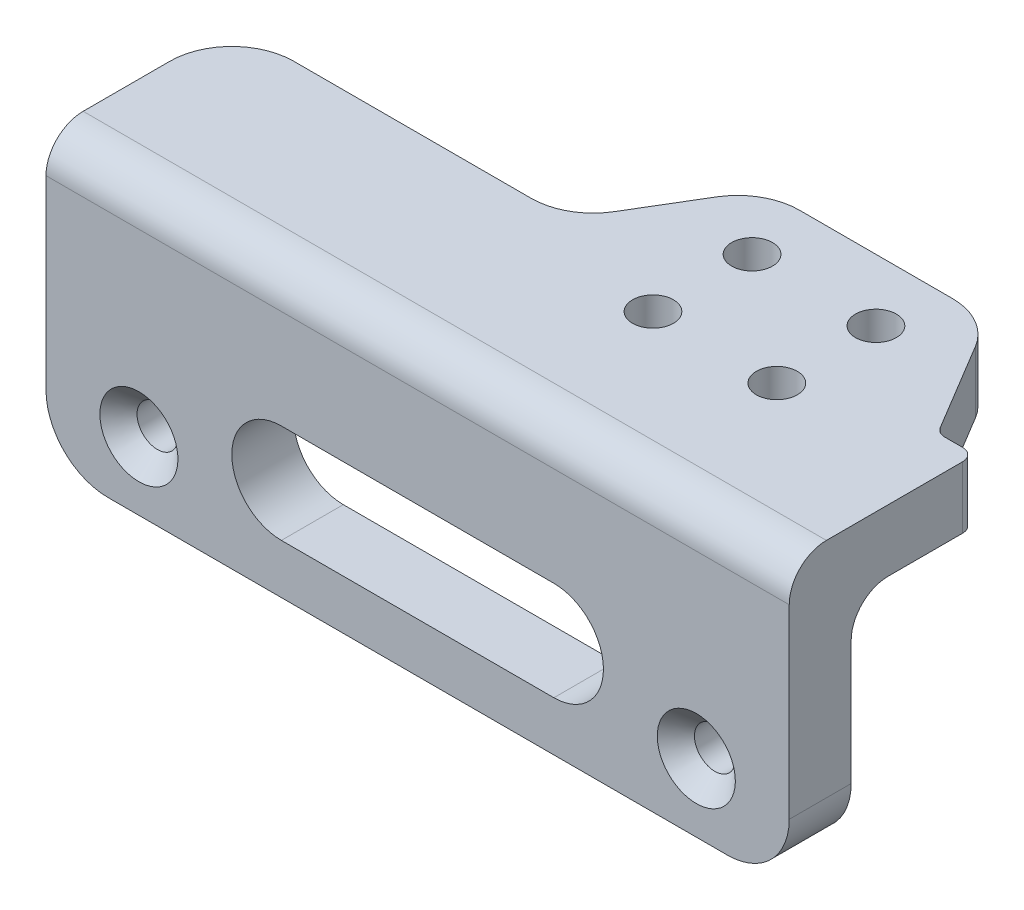
SolidWorks part; units mm, degrees
ref_plane "Front Plane" through (0, 0, 0) normal (0, 0, 1) x (1, 0, 0)
ref_plane "Top Plane" through (0, 0, 0) normal (0, 1, 0) x (1, 0, 0)
ref_plane "Right Plane" through (0, 0, 0) normal (1, 0, 0) x (0, 0, -1)
sketch "Sketch1" plane through (0, 0, 0) normal (1, 0, 0) x (0, 0, -1)
  line L0 (0, 0) -> (20, 0)
  line L1 (0, 0) -> (0, -18)
  line L2 (0, -18) -> (-5, -18)
  line L3 (-5, -18) -> (-5, 5)
  line L4 (-5, 5) -> (20, 5)
  line L5 (20, 5) -> (20, 0)
  dimension "D1" = 5
  dimension "D2" = 20
  dimension "D3" = 18
extrude "Boss-Extrude1" add sketch "Sketch1" along normal mid plane 60
sketch "Sketch2" plane through (0, 0, 0) normal (0, 0, 1) x (1, 0, 0)
  line L0 (0, 0) -> (0, -18) construction
  line L1 (30, -18) -> (-30, -18) construction
  line L2 (30, 0) -> (-30, 0) construction
  circle A0 centre (22.5, -12.5) radius 1.65
  circle A1 centre (-22.5, -12.5) radius 1.65
  dimension "D2" = 3.3
  dimension "D1" = 45
  dimension "D3" = 12.5
extrude "Cut-Extrude1" cut sketch "Sketch2" against normal through all both and the other way through all
sketch "Sketch3" plane through (0, 0, 0) normal (0, 1, 0) x (1, 0, 0)
  line L0 (30, 0) -> (-30, 0) construction
  line L1 (21, 20) -> (27, 10)
  line L2 (-30, 10) -> (-3, 10)
  line L3 (-30, 0) -> (-30, 20) construction
  line L6 (21, 20) -> (3, 20)
  line L7 (-30, 10) -> (-37.048, 19.0463)
  line L8 (-37.048, 19.0463) -> (-34.4811, 29.5471)
  line L9 (-34.4811, 29.5471) -> (-3.2119, 31.8223)
  line L10 (-3.2119, 31.8223) -> (14.2202, 36.9295)
  line L11 (14.2202, 36.9295) -> (36.3515, 35.2735)
  line L12 (36.3515, 35.2735) -> (38.2334, 24.1325)
  line L14 (7, 7) -> (17, 7) construction
  line L15 (7, 7) -> (7, 15) construction
  line L16 (7, 15) -> (17, 15) construction
  line L17 (17, 7) -> (17, 15) construction
  line L18 (7, 7) -> (17, 15) construction
  line L19 (7, 15) -> (17, 7) construction
  line L20 (27, 10) -> (30, 10)
  line L21 (30, 0) -> (30, 20) construction
  line L22 (30, 10) -> (38.2334, 24.1325)
  line L23 (12, 11) -> (12, 20) construction
  line L24 (3, 20) -> (-3, 10)
  circle A4 centre (7, 7) radius 1.65
  circle A5 centre (17, 7) radius 1.65
  circle A6 centre (17, 15) radius 1.65
  circle A7 centre (7, 15) radius 1.65
  point P0 (12, 11)
  point P5 (12, 20)
  dimension "D1" = 12
  dimension "D2" = 11
  dimension "D3" = 8
  dimension "D4" = 10
  dimension "D8" = 3.3
  dimension "D5" = 30
  dimension "D6" = 20
  dimension "D7" = 10
  dimension "D9" = 18
extrude "Cut-Extrude2" cut sketch "Sketch3" against normal through all both and the other way through all
fillet "Fillet1" radius 5 6 edges at (-30, 2.5, -10) (30, -18, 2.5) (-30, -18, 2.5) (-3, 2.5, -10) (3, 2.5, -20) (21, 2.5, -20)
fillet "Fillet2" radius 3 2 edges at (0, 0, 0) (0, 5, 5)
chamfer "Chamfer1" distance 2 angle 45 4 edges at (17, 0, -13.35) (17, 0, -5.35) (7, 0, -13.35) (7, 0, -5.35)
chamfer "Chamfer2" distance 1.5 angle 45 2 edges at (24.15, -12.5, 5) (-24.15, -12.5, 5)
sketch "Sketch4" plane through (0, 0, 5) normal (0, 0, 1) x (1, 0, 0)
  line L0 (-11, -10) -> (11, -10) construction
  line L1 (-11, -6) -> (11, -6)
  line L2 (-11, -14) -> (11, -14)
  arc A0 (-11, -6) -> (-11, -14) centre (-11, -10) ccw
  arc A1 (11, -14) -> (11, -6) centre (11, -10) ccw
  point P2 (0, -10)
  dimension "D1" = 22
  dimension "D2" = 8
  dimension "D3" = 10
extrude "Cut-Extrude3" cut sketch "Sketch4" against normal through all both and the other way through all
fillet "Fillet3" radius 1 2 edges at (27, 2.5, -10) (30, 2.5, -10)
